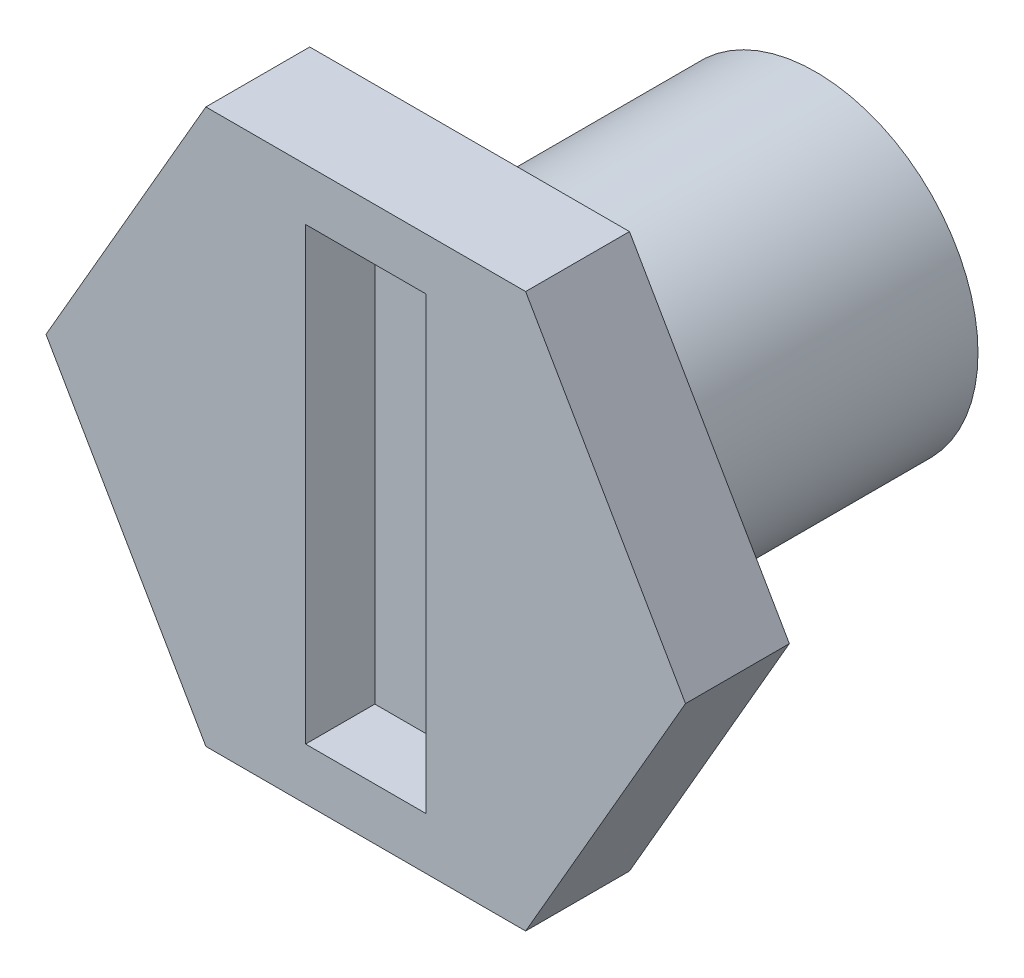
SolidWorks part; units mm, degrees
ref_plane "Front Plane" through (0, 0, 0) normal (0, 0, 1) x (1, 0, 0)
ref_plane "Top Plane" through (0, 0, 0) normal (0, 1, 0) x (1, 0, 0)
ref_plane "Right Plane" through (0, 0, 0) normal (1, 0, 0) x (0, 0, -1)
sketch "Sketch1" plane through (0, 0, 0) normal (0, 0, 1) x (1, 0, 0)
  circle A0 centre (0, 0) radius 46.875
  dimension "D1" = 93.75
extrude "Boss-Extrude1" add sketch "Sketch1" along normal blind 100
sketch "Sketch2" plane through (0, 0, 100) normal (0, 0, 1) x (1, 0, 0)
  line L1 (92.376, 0) -> (46.188, 80)
  line L2 (46.188, 80) -> (-46.188, 80)
  line L3 (-46.188, 80) -> (-92.376, 0)
  line L4 (-92.376, 0) -> (-46.188, -80)
  line L5 (-46.188, -80) -> (46.188, -80)
  line L6 (46.188, -80) -> (92.376, 0)
  circle A0 centre (0, 0) radius 80 construction
  dimension "D1" = 160
extrude "Boss-Extrude2" add sketch "Sketch2" along normal blind 30
sketch "Sketch3" plane through (0, 0, 130) normal (0, 0, 1) x (1, 0, 0)
  line L0 (46.188, 80) -> (-46.188, 80) construction
  line L1 (-17.376, 65) -> (17.376, 65)
  line L2 (-17.376, 65) -> (-17.376, -65)
  line L3 (-17.376, -65) -> (17.376, -65)
  line L4 (17.376, 65) -> (17.376, -65)
  line L5 (-46.188, -80) -> (46.188, -80) construction
  dimension "D1" = 15
  dimension "D2" = 15
  dimension "D3" = 75
  dimension "D4" = 75
extrude "Cut-Extrude1" cut sketch "Sketch3" against normal blind 20
